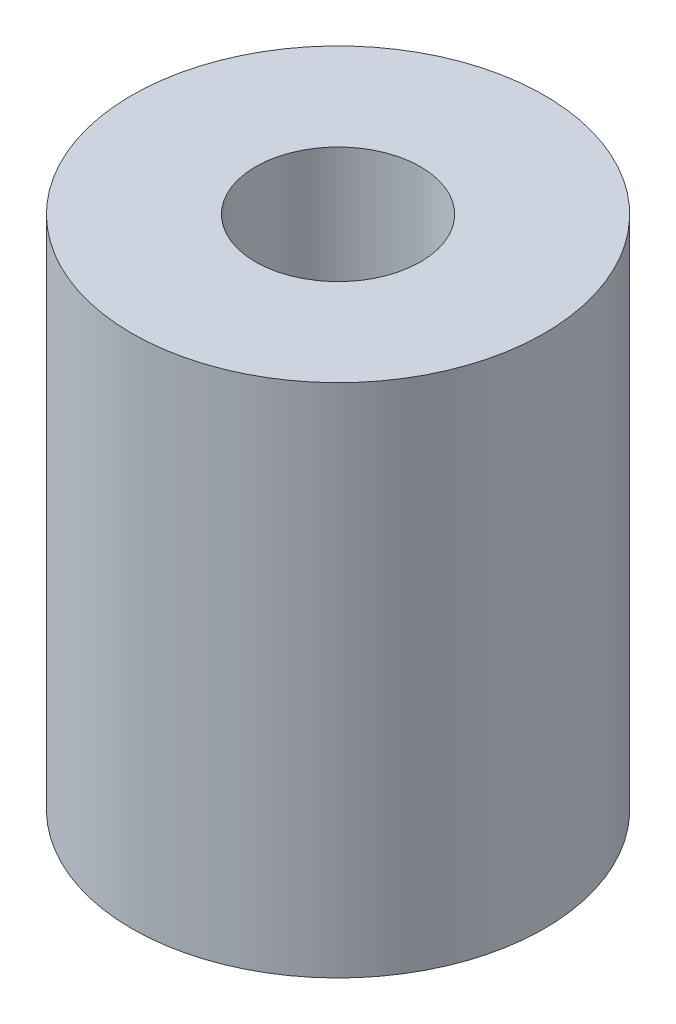
SolidWorks part; units mm, degrees
material "不锈钢 (铁素体)"
ref_plane "前视基准面" through (0, 0, 0) normal (0, 0, 1) x (1, 0, 0)
ref_plane "上视基准面" through (0, 0, 0) normal (0, 1, 0) x (1, 0, 0)
ref_plane "右视基准面" through (0, 0, 0) normal (1, 0, 0) x (0, 0, -1)
sketch "草图1" plane through (0, 0, 0) normal (0, 1, 0) x (1, 0, 0)
  circle A0 centre (0, 0) radius 2.5
  circle A1 centre (0, 0) radius 10
  dimension "D1" = 5
  dimension "D2" = 20
extrude "凸台-拉伸1" add sketch "草图1" along normal blind 12.5
ref_plane "基准面1" through (0, 12.5, 0) normal (0, 1, 0) x (1, 0, 0)
sketch "草图2" plane through (0, 12.5, 0) normal (0, 1, 0) x (1, 0, 0)
  circle A0 centre (0, 0) radius 4
  circle A1 centre (0, 0) radius 10
  dimension "D1" = 8
  dimension "D2" = 20
extrude "凸台-拉伸2" add sketch "草图2" along normal blind 12.5
